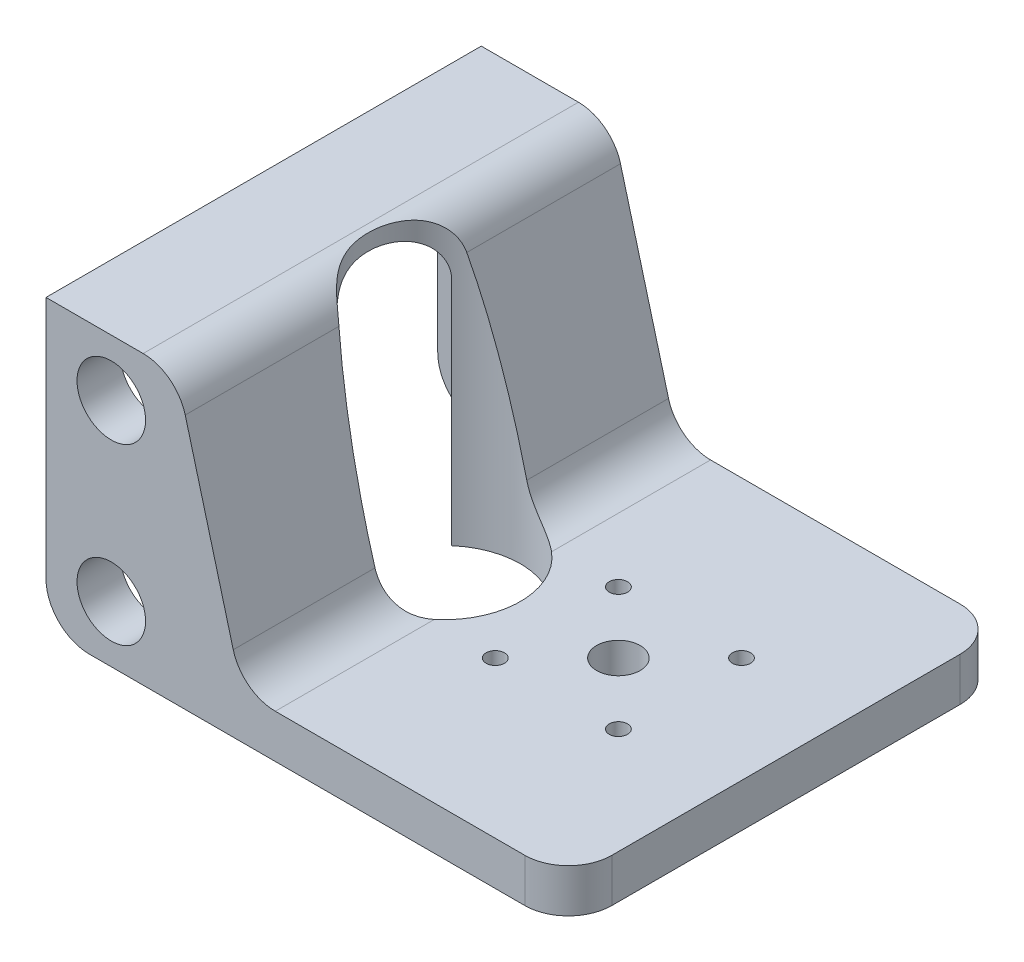
SolidWorks part; units mm, degrees
ref_plane "Front" through (0, 0, 0) normal (0, 0, 1) x (1, 0, 0)
ref_plane "Top" through (0, 0, 0) normal (0, 1, 0) x (1, 0, 0)
ref_plane "Right" through (0, 0, 0) normal (1, 0, 0) x (0, 0, -1)
sketch "Sketch1" plane through (0, 0, 0) normal (0, 0, 1) x (1, 0, 0)
  line L1 (-15, 13) -> (15, 13)
  line L2 (-15, 13) -> (-15, -53)
  line L3 (-15, -53) -> (15, -53)
  line L4 (15, 13) -> (15, -53)
  circle A0 centre (0, 0) radius 7.875
  circle A1 centre (0, -40) radius 7.875
  point P9 (0, 13)
  dimension "D1" = 15.75
  dimension "D2" = 40
  dimension "D3" = 13
  dimension "D4" = 13
  dimension "D5" = 30
extrude "Boss-Extrude1" add sketch "Sketch1" along normal mid plane 100
sketch "Sketch2" plane through (15, 0, 0) normal (1, 0, 0) x (0, 0, -1)
  line L0 (-50, -53) -> (50, -53) construction
  line L1 (-40, -53) -> (40, -53)
  line L2 (-40, -53) -> (-40, 10)
  line L3 (-40, 10) -> (40, 10)
  line L4 (40, -53) -> (40, 10)
  line L5 (-50, 13) -> (50, 13) construction
  point P8 (0, 10)
  dimension "D1" = 3
  dimension "D2" = 80
extrude "Cut-Extrude1" cut sketch "Sketch2" against normal through all
sketch "Sketch4" plane through (0, 0, 50) normal (0, 0, 1) x (1, 0, 0)
  line L0 (15, 13) -> (30.0052, -43)
  line L1 (30.0052, -43) -> (105, -43)
  line L2 (105, -43) -> (105, -53)
  line L3 (105, -53) -> (15, -53)
  line L4 (15, -53) -> (15, 13)
  dimension "D1" = 10
  dimension "D2" = 15
  dimension "D3" = 90
extrude "Boss-Extrude2" add sketch "Sketch4" against normal up to vertex (100 mm away)
sketch "Sketch5" plane through (0, -43, 0) normal (0, 1, 0) x (1, 0, 0)
  line L0 (15, -50) -> (15, 50) construction
  circle A0 centre (66.5, 0) radius 5
  dimension "D2" = 10
  dimension "D1" = 51.5
extrude "Cut-Extrude2" cut sketch "Sketch5" against normal through all
hole_wizard "M5x0.8 Tapped Hole1" positions "Sketch7" profile "Sketch8" tap size "M5x0.8" standard "ANSI Metric" end condition through all
sketch "Sketch7" plane through (0, -43, 0) normal (0, 1, 0) x (1, 0, 0)
  line L0 (66.5, 0) -> (66.5, 20) construction
  line L3 (52.3579, -14.1421) -> (80.6421, 14.1421) construction
  line L6 (80.6421, -14.1421) -> (52.3579, 14.1421) construction
  line L7 (105, 50) -> (105, -50) construction
  line L8 (105, -50) -> (30.0052, -50) construction
  circle A0 centre (66.5, 0) radius 20 construction
  point P0 (80.6421, 14.1421)
  point P21 (80.6421, -14.1421)
  point P22 (52.3579, 14.1421)
  point P27 (52.3579, -14.1421)
  dimension "D1" = 40
  dimension "D2" = 45
  dimension "D3" = 45
  dimension "D4" = 38.5
  dimension "D5" = 50
sketch "Sketch8" plane through (80.6421, -43, -14.1421) normal (1, 0, 0) x (0, 0, 1)
  line L0 (0, 0) -> (0, 10.0001)
  line L1 (0, 10.0001) -> (2.1, 10.0001)
  line L2 (2.1, 10.0001) -> (2.1, 0)
  line L5 (2.1, 0) -> (0, 0)
  line L11 (0, -6.35) -> (0, 107.95) construction
  dimension "Thread Major Dia." = 4.2
  dimension "Thru Tap Drill Depth" = 10.0001
fillet "Fillet1" radius 10 7 edges at (15, 13, 0) (30.0052, -43, 0) (105, -48, 50) (105, -48, -50) (-15, -53, -45) (-15, -53, 45) (15, 10, 0)
sketch "Sketch10" plane through (0, 13, 0) normal (0, 1, 0) x (1, 0, 0)
  line L0 (-15, -50) -> (-15, 50) construction
  circle A0 centre (26.5, 0) radius 17.5
  dimension "D2" = 35
  dimension "D1" = 41.5
extrude "Cut-Extrude3" cut sketch "Sketch10" against normal through all
